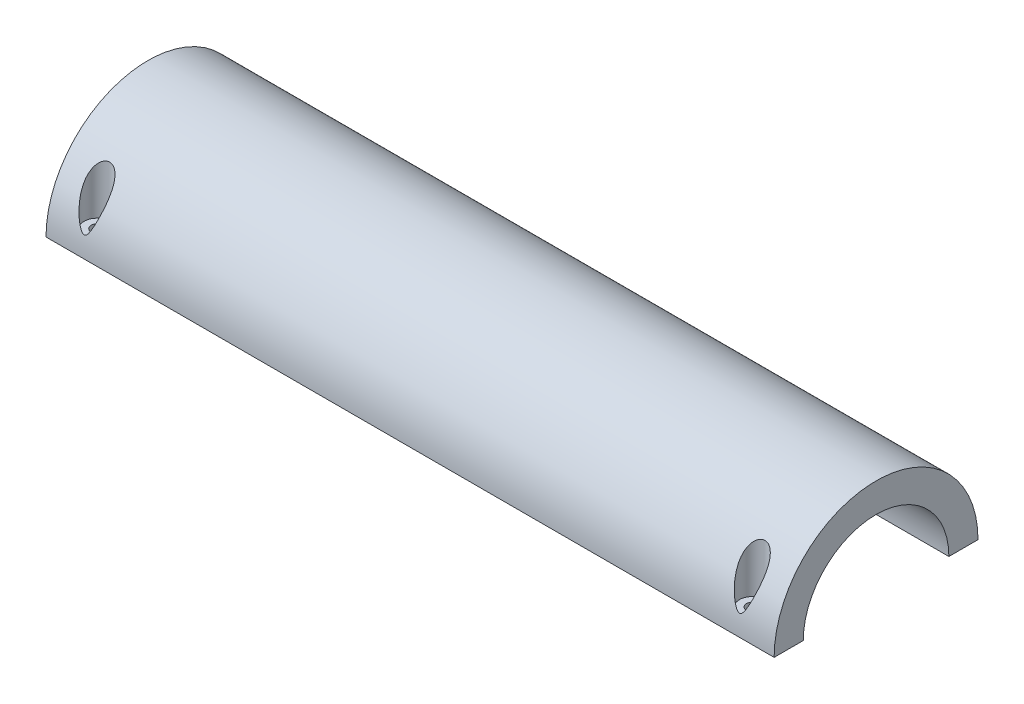
SolidWorks part; units mm, degrees
ref_plane "Ebene vorne" through (0, 0, 0) normal (0, 0, 1) x (1, 0, 0)
ref_plane "Ebene oben" through (0, 0, 0) normal (0, 1, 0) x (1, 0, 0)
ref_plane "Ebene rechts" through (0, 0, 0) normal (1, 0, 0) x (0, 0, -1)
sketch "Skizze1" plane through (0, 0, 0) normal (1, 0, 0) x (0, 0, -1)
  line L0 (-28, 0) -> (-20, 0)
  line L1 (20, 0) -> (28, 0)
  line L2 (0, 0) -> (-20, 0) construction
  line L3 (0, 0) -> (20, 0) construction
  arc A0 (-20, 0) -> (20, 0) centre (0, 0) cw
  arc A1 (-28, 0) -> (28, 0) centre (0, 0) cw
  dimension "D1" = 20
  dimension "D2" = 28
extrude "Aufsatz-Linear austragen1" add sketch "Skizze1" along normal blind 200
sketch "Skizze2" plane through (0, 0, 0) normal (0, -1, 0) x (1, 0, 0)
  line L0 (0, 0) -> (200, 0) construction
  line L1 (200, -20) -> (200, 20) construction
  line L2 (100, 0) -> (100, 28) construction
  line L3 (200, 28) -> (0, 28) construction
  line L4 (100, 24) -> (0, 24) construction
  line L5 (0, 28) -> (0, 20) construction
  circle A0 centre (10, 24) radius 1.6
  circle A1 centre (190, 24) radius 1.6
  circle A2 centre (190, -24) radius 1.6
  circle A3 centre (10, -24) radius 1.6
  dimension "D2" = 3.2
  dimension "D1" = 4
  dimension "D3" = 10
extrude "Schnitt-Linear austragen1" cut sketch "Skizze2" against normal through all
sketch "Skizze3" plane through (0, 0, 0) normal (0, -1, 0) x (1, 0, 0)
  circle A0 centre (10, 24) radius 3.5
  circle A1 centre (190, 24) radius 3.5
  circle A2 centre (190, -24) radius 3.5
  circle A3 centre (10, -24) radius 3.5
  dimension "D1" = 7
  dimension "D2" = 7
  dimension "D3" = 7
  dimension "D4" = 7
extrude "Schnitt-Linear austragen2" cut sketch "Skizze3" against normal through all from offset 5
